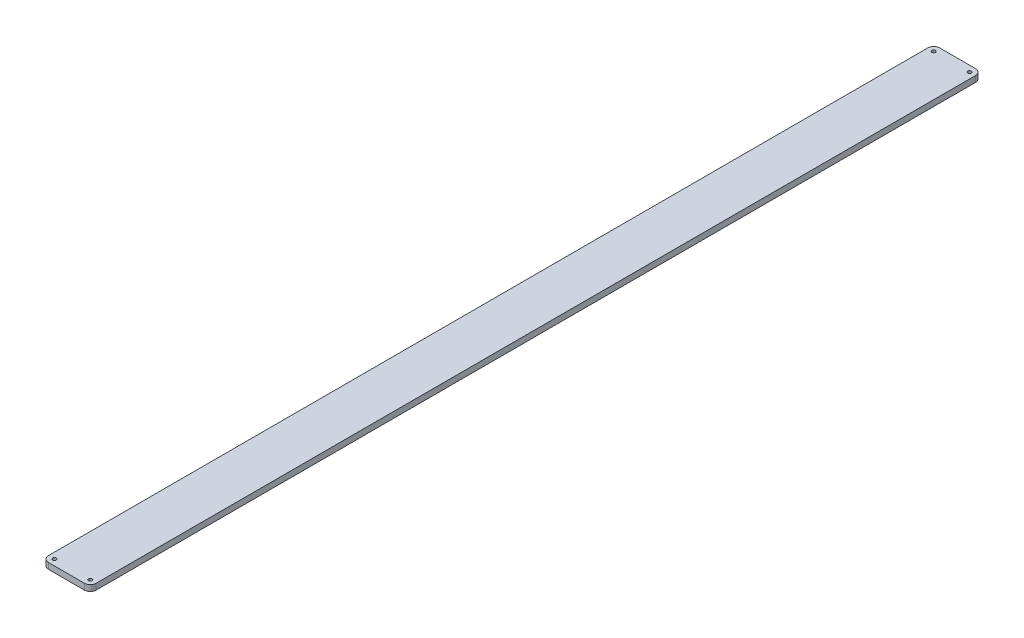
SolidWorks part; units mm, degrees
material "プラ段"
ref_plane "正面" through (0, 0, 0) normal (0, 0, 1) x (1, 0, 0)
ref_plane "平面" through (0, 0, 0) normal (0, 1, 0) x (1, 0, 0)
ref_plane "右側面" through (0, 0, 0) normal (1, 0, 0) x (0, 0, -1)
sketch "ｽｹｯﾁ1" plane through (0, 0, 0) normal (0, 1, 0) x (1, 0, 0)
  line L0 (0, 373) -> (0, -373) construction
  line L1 (-20, -373) -> (20, -373)
  line L2 (-20, -373) -> (-20, 373)
  line L3 (-20, 373) -> (20, 373)
  line L4 (20, -373) -> (20, 373)
  line L5 (-20, -373) -> (20, 373) construction
  line L6 (-20, 373) -> (20, -373) construction
  line L7 (-20, 0) -> (20, 0) construction
  circle A0 centre (15, 368) radius 1.5
  circle A1 centre (-15, 368) radius 1.5
  circle A2 centre (-15, -368) radius 1.5
  circle A3 centre (15, -368) radius 1.5
  point P0 (0, 0)
  dimension "D1" = 30
  dimension "D2" = 736
  dimension "D4" = 5
  dimension "D5" = 3
  dimension "D3" = 5
extrude "ﾎﾞｽ - 押し出し1" add sketch "ｽｹｯﾁ1" along normal blind 5
fillet "ﾌｨﾚｯﾄ1" radius 5 4 edges at (-20, 2.5, -373) (20, 2.5, -373) (-20, 2.5, 373) (20, 2.5, 373)
